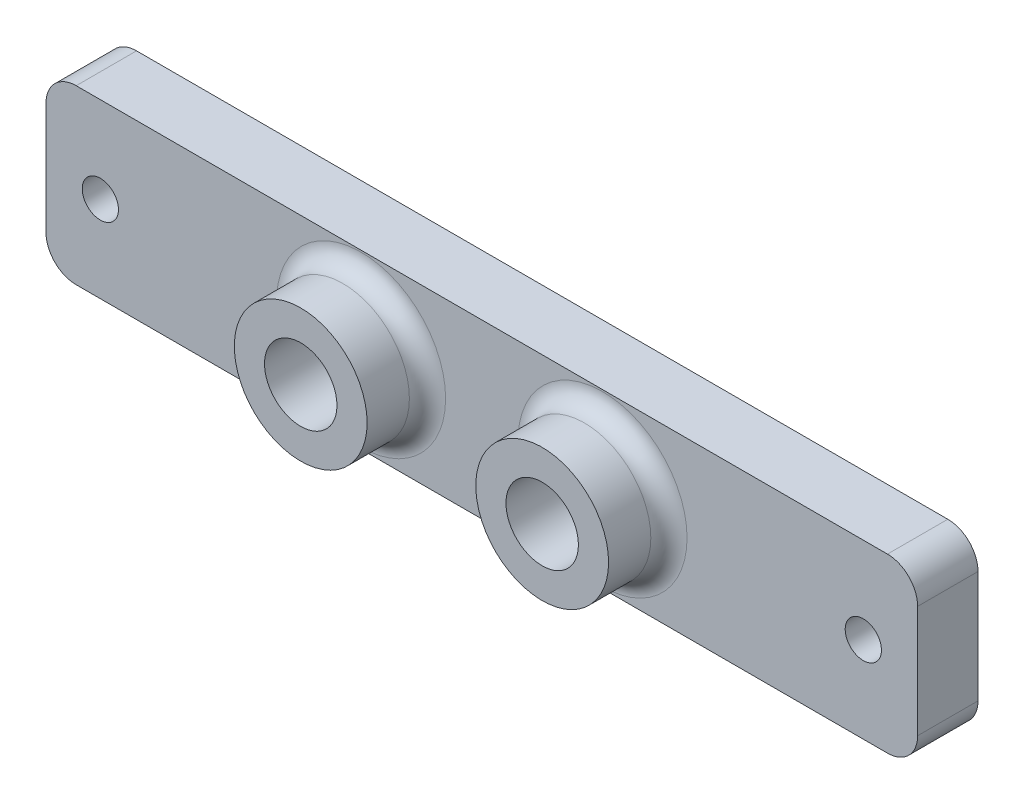
SolidWorks part; units mm, degrees
ref_plane "前视基准面" through (0, 0, 0) normal (0, 0, 1) x (1, 0, 0)
ref_plane "上视基准面" through (0, 0, 0) normal (0, 1, 0) x (1, 0, 0)
ref_plane "右视基准面" through (0, 0, 0) normal (1, 0, 0) x (0, 0, -1)
sketch "草图1" plane through (0, 0, 0) normal (0, 0, 1) x (1, 0, 0)
  line L2 (0, 0) -> (0, 3.14)
  line L6 (36.1, -7.14) -> (-36.1, -7.14)
  line L7 (36.1, -7.14) -> (36.1, 7.14)
  line L8 (36.1, 7.14) -> (-36.1, 7.14)
  line L9 (-36.1, -7.14) -> (-36.1, 7.14)
  circle A0 centre (31.6, 0) radius 1.5
  circle A1 centre (-31.6, 0) radius 1.5
  circle A2 centre (10, 0) radius 3
  circle A3 centre (-10, 0) radius 3
extrude "凸台-拉伸1" add sketch "草图1" along normal blind 5
fillet "圆角1" radius 2.5 4 edges at (36.1, -7.14, 2.5) (-36.1, -7.14, 2.5) (-36.1, 7.14, 2.5) (36.1, 7.14, 2.5)
sketch "草图2" plane through (0, 0, 5) normal (0, 0, 1) x (1, 0, 0)
  circle A0 centre (10, 0) radius 3 construction
  circle A1 centre (-10, 0) radius 3 construction
  circle A2 centre (10, 0) radius 3
  circle A3 centre (-10, 0) radius 3
  circle A4 centre (-10, 0) radius 5.5
  circle A5 centre (10, 0) radius 5.5
  dimension "D1" = 2.5
extrude "凸台-拉伸2" add sketch "草图2" along normal blind 5
fillet "圆角2" radius 1.5 2 edges at (15.5, 0, 5) (-4.5, 0, 5)
